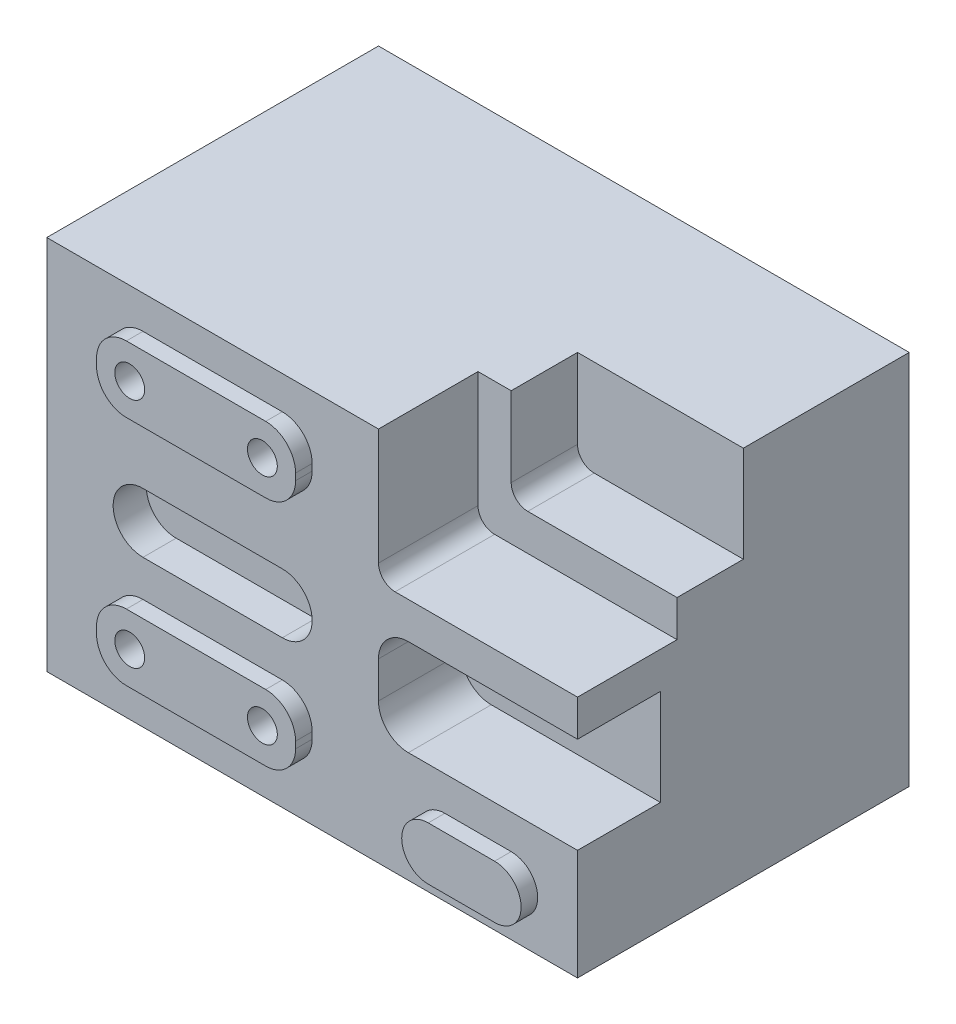
SolidWorks part; units mm, degrees
ref_plane "Plane1" through (0, 0, 0) normal (0, 0, 1) x (1, 0, 0)
ref_plane "Plane2" through (0, 0, 0) normal (0, 1, 0) x (1, 0, 0)
ref_plane "Plane3" through (0, 0, 0) normal (1, 0, 0) x (0, 0, -1)
sketch "Sketch1" plane through (0, 0, 0) normal (0, 0, 1) x (1, 0, 0)
  line L0 (-80, 60) -> (80, 60)
  line L1 (-80, 60) -> (-80, -53.3333)
  line L2 (80, -53.3333) -> (-80, -53.3333)
  line L3 (80, -53.3333) -> (80, 60)
extrude "Base-Extrude" add sketch "Sketch1" against normal blind 100
sketch "Sketch2" plane through (0, 0, 0) normal (0, 0, 1) x (1, 0, 0)
  line L0 (-51, -20) -> (-9, -20)
  line L1 (-60, -29) -> (-60, -31)
  line L2 (-9, -40) -> (-51, -40)
  line L3 (0, -31) -> (0, -29)
  line L4 (-51, 50) -> (-9, 50)
  line L5 (-60, 41) -> (-60, 39)
  line L6 (-9, 30) -> (-51, 30)
  line L7 (0, 39) -> (0, 41)
  line L8 (60, -30.3333) -> (40, -30.3333)
  line L9 (60, -46.3333) -> (40, -46.3333)
  line L10 (80, -53.3333) -> (-80, -53.3333) construction
  arc A0 (40, -30.3333) -> (40, -46.3333) centre (40, -38.3333) ccw
  arc A1 (60, -46.3333) -> (60, -30.3333) centre (60, -38.3333) ccw
  arc A2 (0, -29) -> (-9, -20) centre (-9, -29) ccw
  arc A3 (0, -31) -> (-9, -40) centre (-9, -31) cw
  arc A4 (-60, -29) -> (-51, -20) centre (-51, -29) cw
  arc A5 (-51, -40) -> (-60, -31) centre (-51, -31) cw
  arc A6 (-60, 41) -> (-51, 50) centre (-51, 41) cw
  arc A7 (-51, 30) -> (-60, 39) centre (-51, 39) cw
  arc A8 (0, 39) -> (-9, 30) centre (-9, 39) cw
  arc A9 (0, 41) -> (-9, 50) centre (-9, 41) ccw
  dimension "D1" = 16
  dimension "D2" = 16
  dimension "D3" = 9
  dimension "D4" = 15
extrude "Boss-Extrude1" add sketch "Sketch2" along normal blind 5
sketch "Sketch3" plane through (0, 0, 0) normal (0, 0, 1) x (1, 0, 0)
  line L0 (-9, 9) -> (-51, 9)
  line L1 (-51, -9) -> (-9, -9)
  arc A0 (-51, 9) -> (-51, -9) centre (-51, 0) ccw
  arc A1 (-9, -9) -> (-9, 9) centre (-9, 0) ccw
  dimension "D1" = 18
  dimension "D2" = 18
  dimension "D3" = 9
extrude "Cut-Extrude1" cut sketch "Sketch3" against normal blind 10
sketch "Sketch4" plane through (0, 0, 0) normal (0, 0, 1) x (1, 0, 0)
  line L0 (20, 80) -> (93.3333, 80)
  line L1 (20, 80) -> (20, 25)
  line L2 (93.3333, 20) -> (25, 20)
  line L3 (93.3333, 20) -> (93.3333, 80)
  arc A0 (25, 20) -> (20, 25) centre (25, 25) cw
  dimension "D1" = 5
extrude "Cut-Extrude2" cut sketch "Sketch4" against normal blind 30
sketch "Sketch5" plane through (0, 0, -30) normal (0, 0, 1) x (1, 0, 0)
  line L0 (30, 70) -> (98.3908, 70)
  line L1 (30, 70) -> (30, 36)
  line L2 (98.3908, 31) -> (35, 31)
  line L3 (98.3908, 31) -> (98.3908, 70)
  arc A0 (35, 31) -> (30, 36) centre (35, 36) cw
  dimension "D1" = 5
extrude "Cut-Extrude3" cut sketch "Sketch5" against normal blind 20
sketch "Sketch7" plane through (0, 0, 5) normal (0, 0, 1) x (1, 0, 0)
  circle A0 centre (-50, -30) radius 4.5
  circle A1 centre (-10, -30) radius 4.5
  circle A2 centre (-50, 40) radius 4.5
  circle A3 centre (-10, 40) radius 4.5
  dimension "D1" = 9
  dimension "D2" = 9
  dimension "D3" = 9
  dimension "D4" = 9
extrude "Cut-Extrude4" cut sketch "Sketch7" against normal through all
sketch "Sketch9" plane through (0, 0, 0) normal (0, 0, 1) x (1, 0, 0)
  line L0 (29, 9) -> (103.3333, 9)
  line L1 (20, 0) -> (20, -11)
  line L2 (103.3333, -20) -> (29, -20)
  line L3 (103.3333, -20) -> (103.3333, 9)
  arc A0 (20, 0) -> (29, 9) centre (29, 0) cw
  arc A1 (29, -20) -> (20, -11) centre (29, -11) cw
  dimension "D1" = 9
extrude "Cut-Extrude5" cut sketch "Sketch9" against normal blind 25
